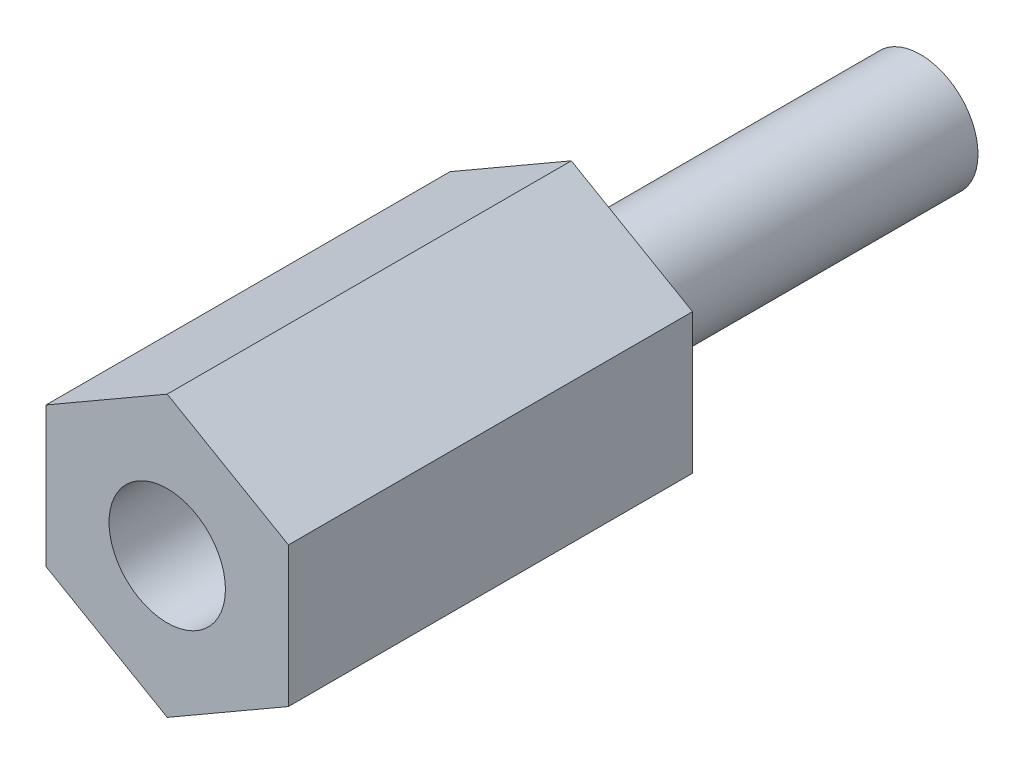
SolidWorks part; units mm, degrees
material "Alloy Steel (SS)"
ref_plane "Front Plane" through (0, 0, 0) normal (0, 0, 1) x (1, 0, 0)
ref_plane "Top Plane" through (0, 0, 0) normal (0, 1, 0) x (1, 0, 0)
ref_plane "Right Plane" through (0, 0, 0) normal (1, 0, 0) x (0, 0, -1)
sketch "Sketch1" plane through (0, 0, 0) normal (0, 0, 1) x (1, 0, 0)
  line L1 (0, 2.7496) -> (-2.3812, 1.3748)
  line L2 (-2.3812, 1.3748) -> (-2.3812, -1.3748)
  line L3 (-2.3812, -1.3748) -> (0, -2.7496)
  line L4 (0, -2.7496) -> (2.3813, -1.3748)
  line L5 (2.3813, -1.3748) -> (2.3812, 1.3748)
  line L6 (2.3812, 1.3748) -> (0, 2.7496)
  circle A0 centre (0, 0) radius 2.3812 construction
  dimension "D1" = 4.7625
extrude "Boss-Extrude1" add sketch "Sketch1" along normal blind 7.9375
sketch "Sketch2" plane through (0, 0, 0) normal (0, 0, -1) x (-1, 0, 0)
  circle A0 centre (0, 0) radius 1.1303
  dimension "D1" = 2.2606
extrude "Boss-Extrude2" add sketch "Sketch2" along normal blind 6.858
sketch "Sketch3" plane through (0, 0, 7.9375) normal (0, 0, 1) x (1, 0, 0)
  circle A0 centre (0, 0) radius 1.143
  dimension "D1" = 2.286
extrude "Cut-Extrude1" cut sketch "Sketch3" against normal blind 2.54
